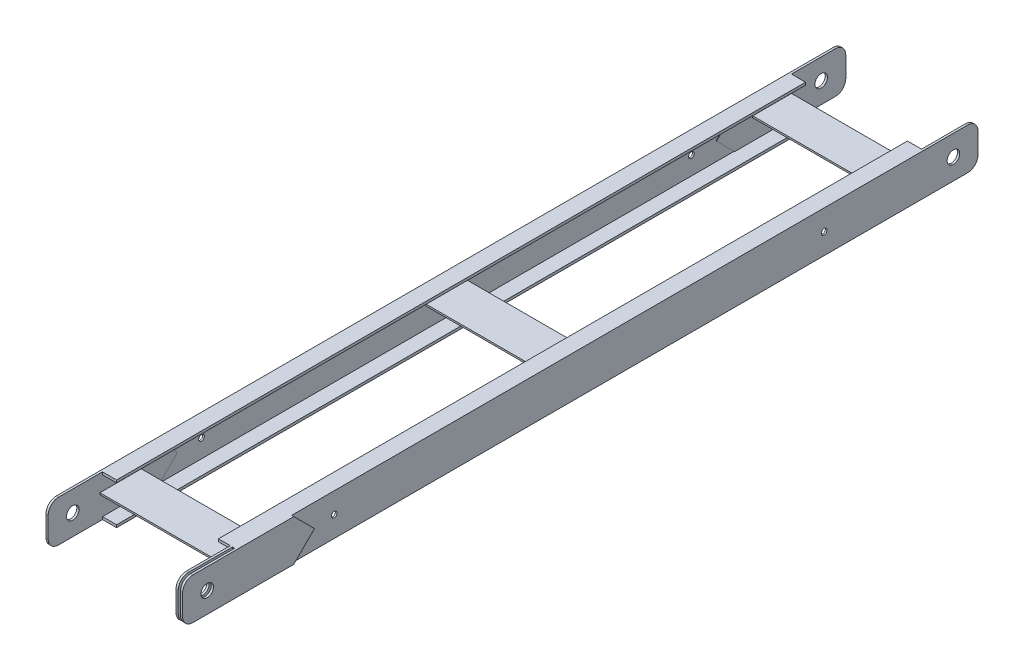
SolidWorks part; units mm, degrees
ref_plane "前视基准面" through (0, 0, 0) normal (0, 0, 1) x (1, 0, 0)
ref_plane "上视基准面" through (0, 0, 0) normal (0, 1, 0) x (1, 0, 0)
ref_plane "右视基准面" through (0, 0, 0) normal (1, 0, 0) x (0, 0, -1)
sketch "草图2" plane through (0, 0, 0) normal (0, 0, 1) x (1, 0, 0)
  line L0 (0, 0) -> (0, 160)
  line L1 (0, 160) -> (63, 160)
  line L2 (63, 160) -> (63, 150)
  line L3 (63, 150) -> (6.5, 150)
  line L4 (6.5, 150) -> (6.5, 10)
  line L5 (6.5, 10) -> (63, 10)
  line L6 (63, 10) -> (63, 0)
  line L7 (63, 0) -> (0, 0)
  line L8 (457, 160) -> (520, 160)
  line L9 (520, 160) -> (520, 0)
  line L10 (520, 0) -> (457, 0)
  line L11 (457, 0) -> (457, 10)
  line L12 (457, 10) -> (513.5, 10)
  line L13 (513.5, 10) -> (513.5, 150)
  line L14 (513.5, 150) -> (457, 150)
  line L15 (457, 150) -> (457, 160)
  dimension "D1" = 160
  dimension "D2" = 10
  dimension "D3" = 6.5
  dimension "D4" = 63
  dimension "D5" = 520
extrude "拉伸1" add sketch "草图2" along normal blind 3085
sketch "草图5" plane through (0, 0, 0) normal (-1, 0, 0) x (0, 0, 1)
  line L0 (200, 95) -> (360, 95)
  line L1 (360, 95) -> (360, 88.5)
  line L2 (283.25, 88.5) -> (360, 88.5)
  line L3 (283.25, 88.5) -> (283.25, 48.5)
  line L4 (283.25, 48.5) -> (276.75, 48.5)
  line L5 (276.75, 48.5) -> (276.75, 88.5)
  line L6 (276.75, 88.5) -> (200, 88.5)
  line L7 (200, 88.5) -> (200, 95)
  line L8 (0, 160) -> (0, 0) construction
  point P10 (0, 80)
  dimension "D1" = 160
  dimension "D2" = 6.5
  dimension "D3" = 6.5
  dimension "D4" = 40
  dimension "D5" = 200
  dimension "D6" = 15
extrude "拉伸3" add sketch "草图5" against normal blind 520
sketch "草图6" plane through (0, 160, 0) normal (0, 1, 0) x (1, 0, 0)
  line L0 (520, 0) -> (457, 0) construction
  line L1 (511.5, 0) -> (8.5, 0)
  line L2 (511.5, 0) -> (511.5, -210)
  line L3 (511.5, -210) -> (8.5, -210)
  line L4 (8.5, 0) -> (8.5, -210)
  line L5 (63, -3085) -> (0, -3085) construction
  line L6 (511.5, -2875) -> (8.5, -2875)
  line L7 (511.5, -2875) -> (511.5, -3085)
  line L8 (511.5, -3085) -> (8.5, -3085)
  line L9 (8.5, -2875) -> (8.5, -3085)
  line L10 (520, -3085) -> (520, 0) construction
  line L11 (0, -3085) -> (0, 0) construction
  dimension "D1" = 8.5
  dimension "D2" = 8.5
  dimension "D3" = 210
  dimension "D4" = 210
  dimension "D5" = 8.5
  dimension "D6" = 8.5
extrude "拉伸4" cut sketch "草图6" against normal through all
pattern_linear "阵列(线性)1" count 3 spacing 1262.5 along (0, 0, 1) of "拉伸3"
sketch "草图7" plane through (513.5, 0, 0) normal (-1, 0, 0) x (0, 0, 1)
  line L0 (3085, 10) -> (0, 10) construction
  line L1 (0, 10) -> (500, 10)
  line L2 (0, 10) -> (0, 150)
  line L3 (0, 150) -> (500, 150)
  line L4 (500, 10) -> (500, 150)
  line L5 (3085, 150) -> (0, 150) construction
  line L6 (3085, 150) -> (3085, 10) construction
  line L7 (3085, 10) -> (2585, 10)
  line L8 (3085, 10) -> (3085, 150)
  line L9 (3085, 150) -> (2585, 150)
  line L10 (2585, 10) -> (2585, 150)
  line L11 (0, 150) -> (0, 10) construction
  dimension "D1" = 500
  dimension "D2" = 500
extrude "拉伸5" add sketch "草图7" along normal blind 2
sketch "草图13" plane through (511.5, 0, 0) normal (-1, 0, 0) x (0, 0, 1)
  line L0 (500, 10) -> (500, 80)
  line L1 (500, 10) -> (500, 150) construction
  line L2 (500, 80) -> (430, 10)
  line L3 (210, 10) -> (500, 10) construction
  line L4 (430, 10) -> (500, 10)
  line L5 (2585, 150) -> (2655, 150)
  line L6 (2875, 150) -> (2585, 150) construction
  line L7 (2655, 150) -> (2585, 80)
  line L8 (2585, 150) -> (2585, 10) construction
  line L9 (2585, 150) -> (2585, 80)
extrude "拉伸6" cut sketch "草图13" against normal blind 2
sketch "草图14" plane through (511.5, 0, 0) normal (-1, 0, 0) x (0, 0, 1)
  line L0 (500, 80) -> (430, 150)
  line L1 (500, 150) -> (210, 150) construction
  line L2 (430, 150) -> (500, 150)
  line L3 (500, 80) -> (500, 150) construction
  line L4 (500, 150) -> (500, 80)
  line L5 (2585, 80) -> (2655, 10)
  line L6 (2585, 10) -> (2875, 10) construction
  line L7 (2655, 10) -> (2585, 10)
  line L8 (2585, 10) -> (2585, 80)
extrude "拉伸7" cut sketch "草图14" against normal blind 2
sketch "草图15" plane through (6.5, 0, 0) normal (1, 0, 0) x (0, 0, -1)
  line L0 (-3085, 10) -> (0, 10) construction
  line L1 (-3085, 150) -> (-2585, 150)
  line L2 (-3085, 150) -> (-3085, 10)
  line L3 (-3085, 10) -> (-2585, 10)
  line L4 (-2585, 150) -> (-2585, 10)
  line L5 (-3085, 150) -> (0, 150) construction
  line L6 (0, 10) -> (0, 150) construction
  line L7 (-500, 150) -> (0, 150)
  line L8 (-500, 150) -> (-500, 10)
  line L9 (-500, 10) -> (0, 10)
  line L10 (0, 150) -> (0, 10)
  dimension "D1" = 500
  dimension "D2" = 500
extrude "拉伸8" add sketch "草图15" along normal blind 2
sketch "草图16" plane through (8.5, 0, 0) normal (1, 0, 0) x (0, 0, -1)
  line L0 (-2585, 150) -> (-2585, 80)
  line L1 (-2585, 10) -> (-2585, 150) construction
  line L2 (-2585, 80) -> (-2655, 150)
  line L3 (-2585, 150) -> (-2875, 150) construction
  line L4 (-2655, 150) -> (-2585, 150)
  line L5 (-500, 150) -> (-500, 80)
  line L6 (-500, 150) -> (-500, 10) construction
  line L7 (-500, 80) -> (-430, 150)
  line L8 (-210, 150) -> (-500, 150) construction
  line L9 (-430, 150) -> (-500, 150)
extrude "拉伸9" cut sketch "草图16" against normal blind 2
sketch "草图18" plane through (8.5, 0, 0) normal (1, 0, 0) x (0, 0, -1)
  line L0 (-500, 80) -> (-500, 10)
  line L1 (-500, 10) -> (-430, 10)
  line L2 (-500, 10) -> (-210, 10) construction
  line L3 (-430, 10) -> (-500, 80)
  line L4 (-2585, 10) -> (-2655, 10)
  line L5 (-2875, 10) -> (-2585, 10) construction
  line L6 (-2655, 10) -> (-2585, 80)
  line L7 (-2585, 80) -> (-2585, 10)
extrude "拉伸10" cut sketch "草图18" against normal blind 2
sketch "草图19" plane through (520, 0, 0) normal (1, 0, 0) x (0, 0, -1)
  line L0 (-3085, 0) -> (0, 0) construction
  line L1 (-3085, 160) -> (-2655, 160)
  line L2 (-3085, 160) -> (-3085, 0)
  line L3 (-3085, 0) -> (-2655, 0)
  line L4 (-2655, 160) -> (-2575, 80)
  line L5 (-2575, 80) -> (-2655, 0)
  dimension "D1" = 430
extrude "拉伸11" add sketch "草图19" along normal blind 8.5
pattern_linear "阵列(线性)2" count 2 spacing 17 along (-1, 0, 0) of "拉伸11"
sketch "草图22" plane through (0, 160, 0) normal (0, 1, 0) x (1, 0, 0)
  line L0 (528.5, -3085) -> (503, -3085) construction
  line L1 (511.5, -2875) -> (520, -2875)
  line L2 (511.5, -2875) -> (511.5, -3085)
  line L3 (511.5, -3085) -> (520, -3085)
  line L4 (520, -2875) -> (520, -3085)
  line L5 (528.5, -2655) -> (528.5, -3085) construction
  line L6 (503, -2875) -> (503, -3085) construction
  line L7 (503, -2875) -> (457, -2875) construction
  dimension "D1" = 8.5
  dimension "D2" = 8.5
extrude "拉伸12" cut sketch "草图22" against normal through all
fillet "圆角1" radius 40 8 edges at (515.75, 0, 0) (515.75, 160, 0) (4.25, 0, 0) (4.25, 160, 0) (4.25, 0, 3085) (4.25, 160, 3085) (507.25, 0, 3085) (507.25, 160, 3085)
sketch "草图23" plane through (0, 0, 0) normal (-1, 0, 0) x (0, 0, 1)
  line L0 (0, 120) -> (0, 40) construction
  line L2 (3045, 0) -> (40, 0) construction
  line L3 (3085, 120) -> (3085, 40) construction
  line L4 (3045, 160) -> (40, 160) construction
  circle A0 centre (95, 80) radius 24.25
  circle A1 centre (2990, 80) radius 24.25
  dimension "D3" = 48.5
  dimension "D4" = 48.5
  dimension "D1" = 95
  dimension "D2" = 80
  dimension "D5" = 95
  dimension "D6" = 80
extrude "拉伸13" cut sketch "草图23" against normal through all
sketch "草图24" plane through (520, 0, 0) normal (1, 0, 0) x (0, 0, -1)
  line L0 (-95, 80) -> (-2990, 80) construction
  circle A0 centre (-2490, 80) radius 11
  circle A1 centre (-595, 80) radius 11
  dimension "D1" = 22
  dimension "D2" = 22
  dimension "D3" = 500
  dimension "D4" = 500
extrude "拉伸14" cut sketch "草图24" against normal through all
